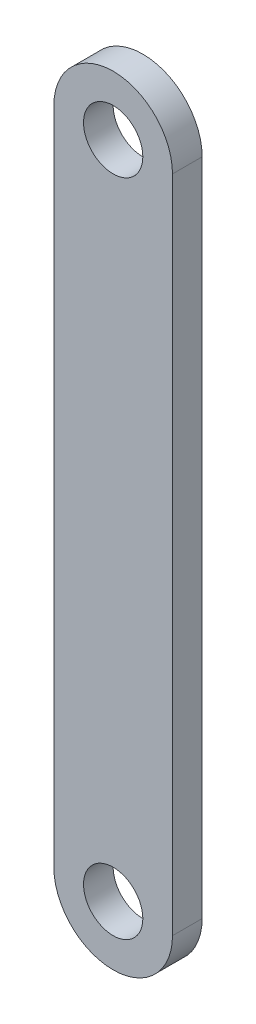
SolidWorks part; units mm, degrees
ref_plane "Спереди" through (0, 0, 0) normal (0, 0, 1) x (1, 0, 0)
ref_plane "Сверху" through (0, 0, 0) normal (0, 1, 0) x (1, 0, 0)
ref_plane "Справа" through (0, 0, 0) normal (1, 0, 0) x (0, 0, -1)
sketch "Model" plane through (0, 0, 0) normal (0, 0, 1) x (1, 0, 0)
  line L0 (0, 22.2444) -> (0, 0) construction
  line L1 (-2, 22.2444) -> (-2, 0)
  line L2 (2, 22.2444) -> (2, 0)
  circle A0 centre (0, 22.2444) radius 1
  arc A5 (2, 22.2444) -> (-2, 22.2444) centre (0, 22.2444) ccw
  arc A6 (-2, 0) -> (2, 0) centre (0, 0) ccw
  circle A8 centre (0, 0) radius 1
extrude "Extrude1" add sketch "Model" along normal blind 1
